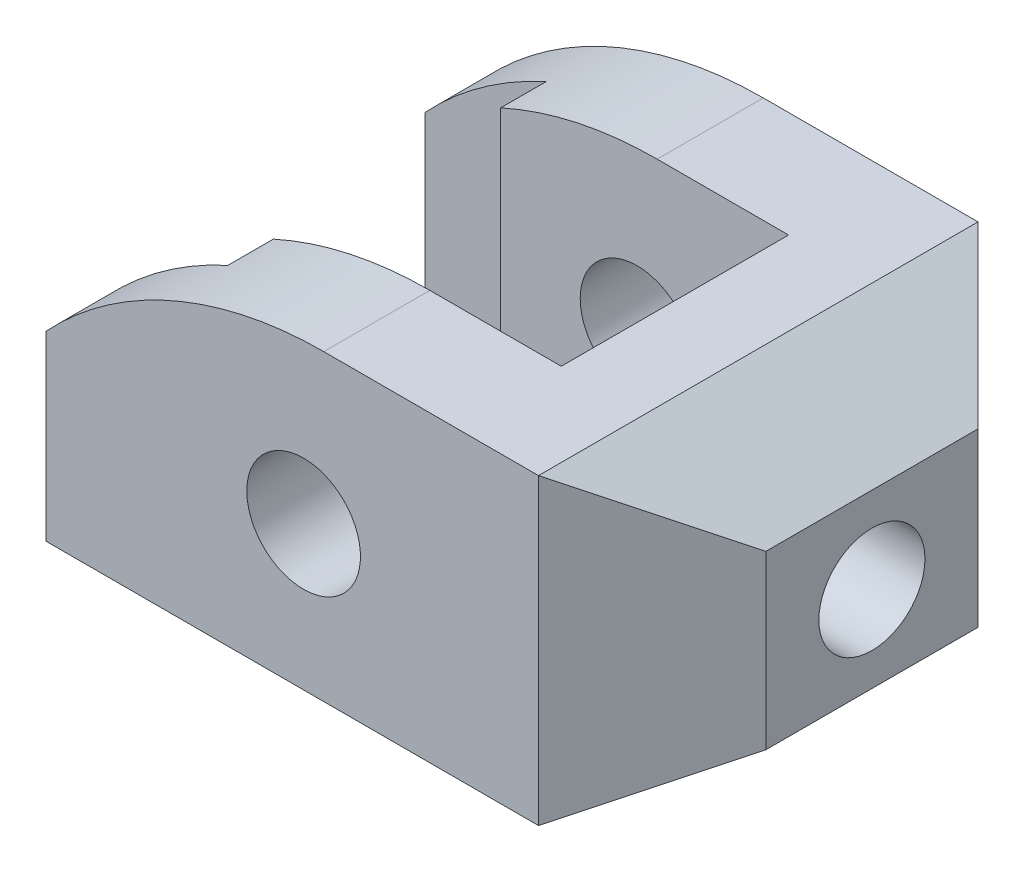
SolidWorks part; units mm, degrees
material "1060 Alloy"
ref_plane "Front Plane" through (0, 0, 0) normal (0, 0, 1) x (1, 0, 0)
ref_plane "Top Plane" through (0, 0, 0) normal (0, 1, 0) x (1, 0, 0)
ref_plane "Right Plane" through (0, 0, 0) normal (1, 0, 0) x (0, 0, -1)
sketch "Sketch1" plane through (0, 0, 0) normal (0, 0, 1) x (1, 0, 0)
  line L0 (0, 0) -> (-65, 0)
  line L1 (0, 0) -> (15, 8.6603)
  line L2 (15, 8.6603) -> (15, 31.3397)
  line L3 (15, 31.3397) -> (0, 40)
  line L4 (0, 40) -> (-28.3394, 40)
  line L5 (-65, 0) -> (-65, 24)
  arc A0 (-65, 24) -> (-28.3394, 40) centre (-28.3394, -10) cw
  circle A2 centre (-31, 19) radius 7.5
  point P11 (0, 0)
  dimension "D3" = 50
  dimension "D2" = 15
  dimension "D1" = 65
  dimension "D4" = 31
  dimension "D5" = 19
  dimension "D6" = 24
  dimension "D7" = 15
  dimension "D8" = 30
  dimension "D9" = 30
  dimension "D10" = 15
  dimension "D11" = 40
extrude "Boss-Extrude1" add sketch "Sketch1" along normal blind 58
ref_plane "Plane2" through (0, 20, 0) normal (0, 1, 0) x (1, 0, 0)
sketch "Sketch3" plane through (0, 20, 0) normal (0, 1, 0) x (1, 0, 0)
  line L0 (15, -29) -> (-80.6381, -29) construction
  line L1 (15, -58) -> (15, 0) construction
  line L2 (-11, -44) -> (-11, -14)
  line L3 (-11, -14) -> (-49, -14)
  line L4 (-49, -14) -> (-49, -8)
  line L5 (-49, -8) -> (-65, -8)
  line L6 (-65, -58) -> (-65, 0) construction
  line L7 (-65, -8) -> (-65, -50)
  line L8 (0, -58) -> (0, 0) construction
  line L9 (-28.3394, 0) -> (-65, 0) construction
  line L10 (-49, -50) -> (-65, -50)
  line L11 (-49, -44) -> (-49, -50)
  line L12 (-11, -44) -> (-49, -44)
  point P17 (-65, -29)
  point P20 (-11, -29)
  dimension "D1" = 11
  dimension "D2" = 16
  dimension "D3" = 6
  dimension "D4" = 8
extrude "Cut-Extrude1" cut sketch "Sketch3" against normal through all both and the other way through all
sketch "Sketch6" plane through (0, 0, 0) normal (0, 1, 0) x (1, 0, 0)
  line L0 (15, -29) -> (0, -29) construction
  line L1 (15, -58) -> (15, 0) construction
  line L2 (0, -58) -> (0, 0) construction
  line L3 (0, 0) -> (15, -15)
  line L4 (0, 0) -> (15, 0)
  line L5 (15, 0) -> (15, -15)
  line L6 (15, -58) -> (15, -43)
  line L7 (0, -58) -> (15, -58)
  line L8 (0, -58) -> (15, -43)
  dimension "D1" = 45
extrude "Cut-Extrude2" cut sketch "Sketch6" along normal through all both and the other way through all
sketch "Sketch7" plane through (15, 0, 0) normal (1, 0, 0) x (0, 0, -1)
  line L0 (0, 20) -> (-58, 20) construction
  line L1 (0, 40) -> (0, 0) construction
  line L2 (-58, 40) -> (-58, 0) construction
  line L3 (-58, 0) -> (0, 0) construction
  line L5 (-29, 40) -> (-29, 0) construction
  line L6 (-58, 40) -> (0, 40) construction
  circle A0 centre (-29, 20) radius 7
  dimension "D3" = 14
  dimension "D1" = 20
  dimension "D2" = 29
extrude "Cut-Extrude3" cut sketch "Sketch7" against normal through all both and the other way through all
equation "\"A\"= 58.00mm"
equation "\"B\"= 40.00mm"
equation "\"C\"= 65.00mm"
equation "\"D1@Sketch1\"=\"C\""
equation "\"D11@Sketch1\"=\"B\""
equation "\"D1@Boss-Extrude1\"=\"A\""
equation "\"D1@Sketch7\"=\"B\"/2"
equation "\"D2@Sketch7\"=\"A\"/2"
